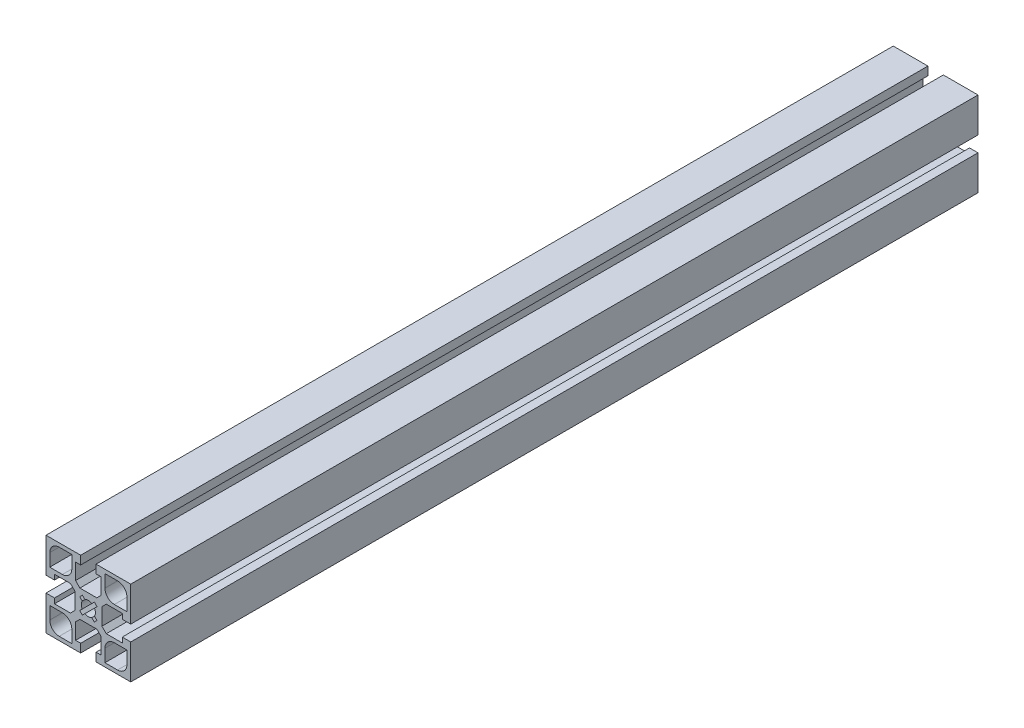
SolidWorks part; units mm, degrees
material "6061 Alloy"
ref_plane "Front Plane" through (0, 0, 0) normal (0, 0, 1) x (1, 0, 0)
ref_plane "Top Plane" through (0, 0, 0) normal (0, 1, 0) x (1, 0, 0)
ref_plane "Right Plane" through (0, 0, 0) normal (1, 0, 0) x (0, 0, -1)
sketch "Sketch1" plane through (0, 0, 0) normal (0, 0, 1) x (1, 0, 0)
  line L4 (-20.5, 8.8) -> (-20.5, 15.5)
  line L5 (-13.8, 8.8) -> (-20.5, 8.8)
  line L6 (-8.8, 20.5) -> (-8.8, 13.8)
  line L7 (-15.5, 20.5) -> (-8.8, 20.5)
  line L12 (20.5, 8.8) -> (13.8, 8.8)
  line L13 (20.5, 15.5) -> (20.5, 8.8)
  line L14 (8.8, 20.5) -> (15.5, 20.5)
  line L15 (8.8, 13.8) -> (8.8, 20.5)
  line L20 (15.5, -20.5) -> (8.8, -20.5)
  line L21 (20.5, -8.8) -> (20.5, -15.5)
  line L22 (13.8, -8.8) -> (20.5, -8.8)
  line L23 (8.8, -20.5) -> (8.8, -13.8)
  line L28 (-8.8, -20.5) -> (-15.5, -20.5)
  line L29 (-8.8, -13.8) -> (-8.8, -20.5)
  line L30 (-20.5, -8.8) -> (-13.8, -8.8)
  line L31 (-20.5, -15.5) -> (-20.5, -8.8)
  line L88 (-18, -6.8) -> (-18, -4.1)
  line L89 (-18, -4.1) -> (-22.5, -4.1)
  line L90 (-22.5, -4.1) -> (-22.5, -22.5)
  line L91 (-22.5, -22.5) -> (-4.1, -22.5)
  line L92 (-4.1, -22.5) -> (-4.1, -18)
  line L93 (-4.1, -18) -> (-6.8, -18)
  line L94 (-6.8, -18) -> (-6.8, -9.5)
  line L95 (-6.8, -9.5) -> (-4.5, -7.2)
  line L96 (-4.5, -7.2) -> (4.5, -7.2)
  line L97 (4.5, -7.2) -> (6.8, -9.5)
  line L98 (6.8, -9.5) -> (6.8, -18)
  line L99 (6.8, -18) -> (4.1, -18)
  line L100 (4.1, -18) -> (4.1, -22.5)
  line L101 (4.1, -22.5) -> (22.5, -22.5)
  line L102 (22.5, -22.5) -> (22.5, -4.1)
  line L103 (22.5, -4.1) -> (18, -4.1)
  line L104 (18, -4.1) -> (18, -6.8)
  line L105 (18, -6.8) -> (9.5, -6.8)
  line L106 (9.5, -6.8) -> (7.2, -4.5)
  line L107 (7.2, -4.5) -> (7.2, 4.5)
  line L108 (7.2, 4.5) -> (9.5, 6.8)
  line L109 (9.5, 6.8) -> (18, 6.8)
  line L110 (18, 6.8) -> (18, 4.1)
  line L111 (18, 4.1) -> (22.5, 4.1)
  line L112 (22.5, 4.1) -> (22.5, 22.5)
  line L113 (22.5, 22.5) -> (4.1, 22.5)
  line L114 (4.1, 22.5) -> (4.1, 18)
  line L115 (4.1, 18) -> (6.8, 18)
  line L116 (6.8, 18) -> (6.8, 9.5)
  line L117 (6.8, 9.5) -> (4.5, 7.2)
  line L118 (4.5, 7.2) -> (-4.5, 7.2)
  line L119 (-4.5, 7.2) -> (-6.8, 9.5)
  line L120 (-6.8, 9.5) -> (-6.8, 18)
  line L121 (-6.8, 18) -> (-4.1, 18)
  line L122 (-4.1, 18) -> (-4.1, 22.5)
  line L123 (-4.1, 22.5) -> (-22.5, 22.5)
  line L124 (-22.5, 22.5) -> (-22.5, 4.1)
  line L125 (-22.5, 4.1) -> (-18, 4.1)
  line L126 (-18, 4.1) -> (-18, 6.8)
  line L127 (-18, 6.8) -> (-9.5, 6.8)
  line L128 (-9.5, 6.8) -> (-7.2, 4.5)
  line L129 (-7.2, 4.5) -> (-7.2, -4.5)
  line L130 (-7.2, -4.5) -> (-9.5, -6.8)
  line L131 (-9.5, -6.8) -> (-18, -6.8)
  line L132 (-3.2627, 1.8485) -> (-4.5962, 3.182)
  line L133 (-4.5962, -3.182) -> (-3.2627, -1.8485)
  line L134 (-3.182, -4.5962) -> (-4.5962, -3.182)
  line L135 (-1.8485, -3.2627) -> (-3.182, -4.5962)
  line L136 (3.182, -4.5962) -> (1.8485, -3.2627)
  line L137 (4.5962, -3.182) -> (3.182, -4.5962)
  line L138 (3.2627, -1.8485) -> (4.5962, -3.182)
  line L139 (4.5962, 3.182) -> (3.2627, 1.8485)
  line L140 (3.182, 4.5962) -> (4.5962, 3.182)
  line L141 (1.8485, 3.2627) -> (3.182, 4.5962)
  line L142 (-3.182, 4.5962) -> (-1.8485, 3.2627)
  line L143 (-4.5962, 3.182) -> (-3.182, 4.5962)
  arc A2 (-13.8, 8.8) -> (-8.8, 13.8) centre (-13.8, 13.8) ccw
  arc A3 (-15.5, 20.5) -> (-20.5, 15.5) centre (-15.5, 15.5) ccw
  arc A6 (8.8, 13.8) -> (13.8, 8.8) centre (13.8, 13.8) ccw
  arc A7 (20.5, 15.5) -> (15.5, 20.5) centre (15.5, 15.5) ccw
  arc A10 (15.5, -20.5) -> (20.5, -15.5) centre (15.5, -15.5) ccw
  arc A11 (13.8, -8.8) -> (8.8, -13.8) centre (13.8, -13.8) ccw
  arc A14 (-20.5, -15.5) -> (-15.5, -20.5) centre (-15.5, -15.5) ccw
  arc A15 (-8.8, -13.8) -> (-13.8, -8.8) centre (-13.8, -13.8) ccw
  arc A20 (-3.2627, 1.8485) -> (-3.2627, -1.8485) centre (0, 0) ccw
  arc A21 (-1.8485, -3.2627) -> (1.8485, -3.2627) centre (0, 0) ccw
  arc A22 (3.2627, -1.8485) -> (3.2627, 1.8485) centre (0, 0) ccw
  arc A23 (1.8485, 3.2627) -> (-1.8485, 3.2627) centre (0, 0) ccw
extrude "Boss-Extrude1" add sketch "Sketch1" along normal blind 300
scale "Scale1" bodies to scale 101 scale about centroid uniform scaling no x scale factor 0.6667 y scale factor 0.6667 z scale factor 1
